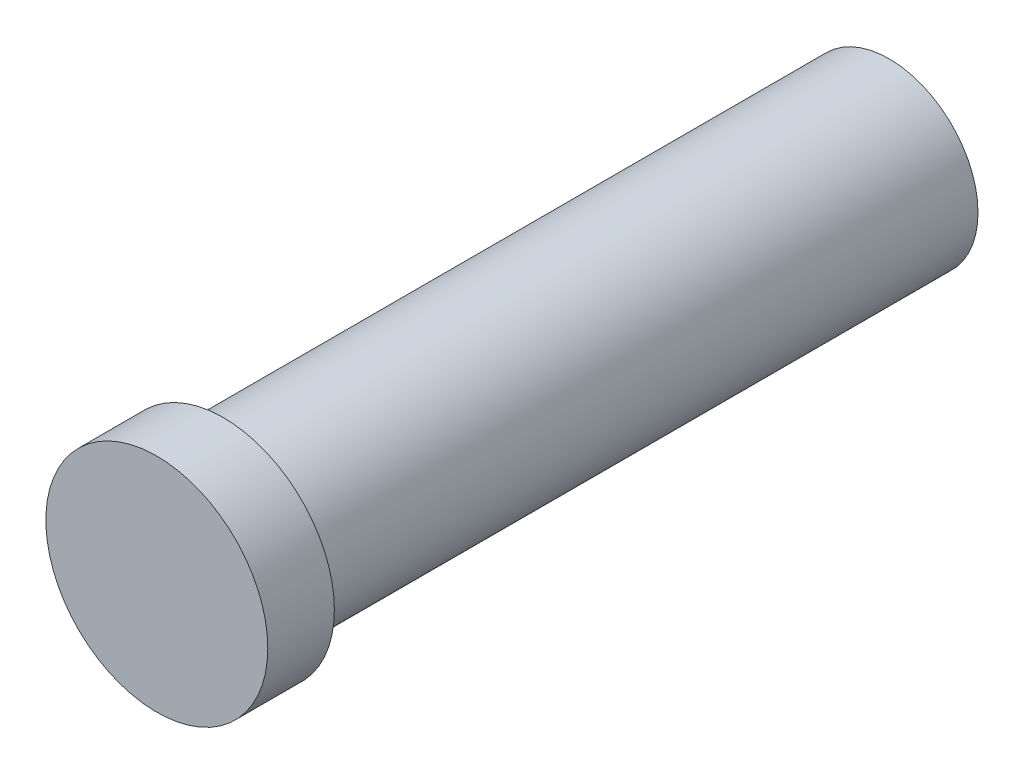
SolidWorks part; units mm, degrees
ref_plane "Ebene vorne" through (0, 0, 0) normal (0, 0, 1) x (1, 0, 0)
ref_plane "Ebene oben" through (0, 0, 0) normal (0, 1, 0) x (1, 0, 0)
ref_plane "Ebene rechts" through (0, 0, 0) normal (1, 0, 0) x (0, 0, -1)
sketch "Skizze1" plane through (0, 0, 0) normal (0, 0, 1) x (1, 0, 0)
  circle A0 centre (0, 0) radius 4
  dimension "D1" = 8
extrude "Aufsatz-Linear austragen1" add sketch "Skizze1" along normal blind 33
sketch "Skizze2" plane through (0, 0, 33) normal (0, 0, 1) x (1, 0, 0)
  circle A0 centre (0, 0) radius 5
extrude "Aufsatz-Linear austragen2" add sketch "Skizze2" against normal blind 3
sketch "Skizze3" plane through (0, 0, 0) normal (0, 0, -1) x (-1, 0, 0)
  circle A0 centre (0, 0) radius 2.25
  dimension "D1" = 4.5
